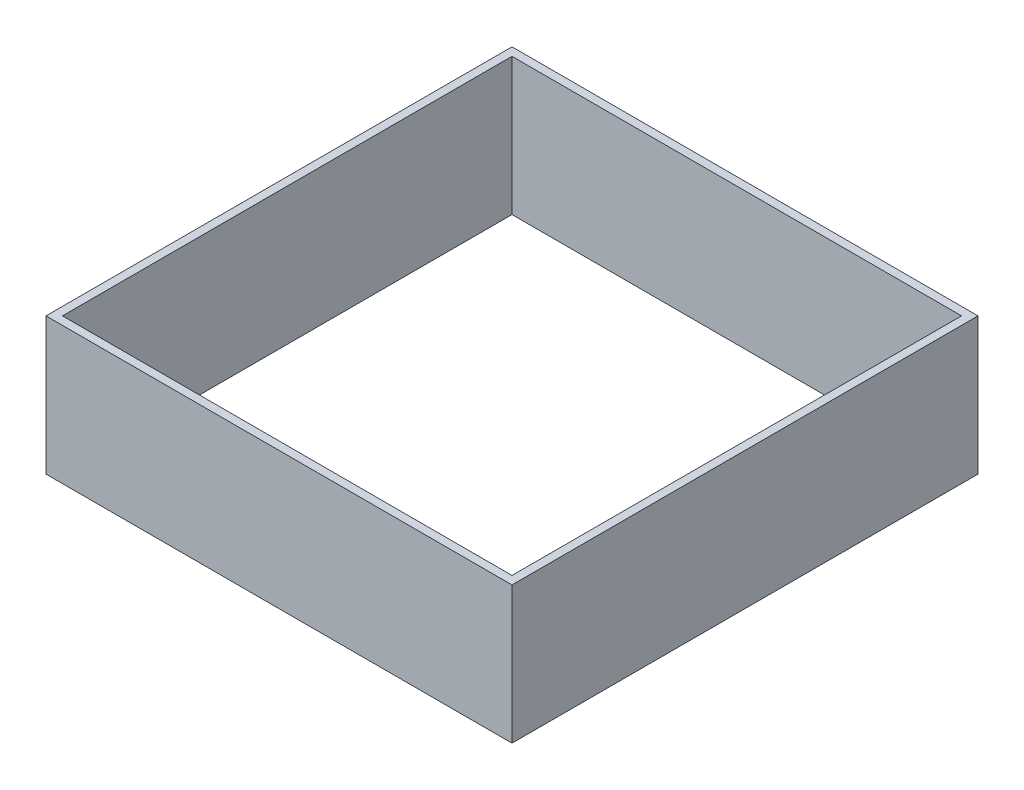
SolidWorks part; units mm, degrees
ref_plane "Front Plane" through (0, 0, 0) normal (0, 0, 1) x (1, 0, 0)
ref_plane "Top Plane" through (0, 0, 0) normal (0, 1, 0) x (1, 0, 0)
ref_plane "Right Plane" through (0, 0, 0) normal (1, 0, 0) x (0, 0, -1)
sketch "Sketch1" plane through (0, 0, 0) normal (0, 1, 0) x (1, 0, 0)
  line L1 (-164, -164) -> (164, -164)
  line L2 (-164, -164) -> (-164, 164)
  line L3 (-164, 164) -> (164, 164)
  line L4 (164, -164) -> (164, 164)
  line L5 (-164, -164) -> (164, 164) construction
  line L6 (-164, 164) -> (164, -164) construction
  line L7 (-170, -170) -> (170, -170)
  line L8 (-170, -170) -> (-170, 170)
  line L9 (-170, 170) -> (170, 170)
  line L10 (170, -170) -> (170, 170)
  line L11 (-170, -170) -> (170, 170) construction
  line L12 (-170, 170) -> (170, -170) construction
  point P0 (0, 0)
  point P6 (0, 0)
  dimension "D1" = 6
  dimension "D2" = 6
  dimension "D3" = 328
extrude "Boss-Extrude1" add sketch "Sketch1" along normal blind 100
